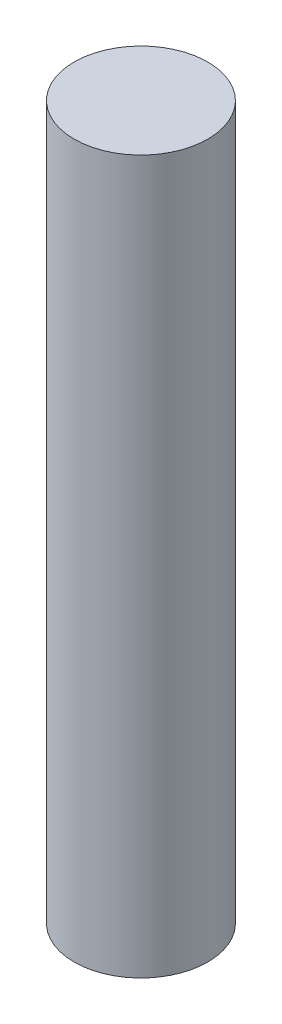
SolidWorks part; units mm, degrees
ref_plane "Front Plane" through (0, 0, 0) normal (0, 0, 1) x (1, 0, 0)
ref_plane "Top Plane" through (0, 0, 0) normal (0, 1, 0) x (1, 0, 0)
ref_plane "Right Plane" through (0, 0, 0) normal (1, 0, 0) x (0, 0, -1)
sketch "Sketch1" plane through (0, 0, 0) normal (0, 1, 0) x (1, 0, 0)
  circle A0 centre (0, 0) radius 7.5
  dimension "D1" = 15
extrude "Boss-Extrude1" add sketch "Sketch1" along normal blind 80
